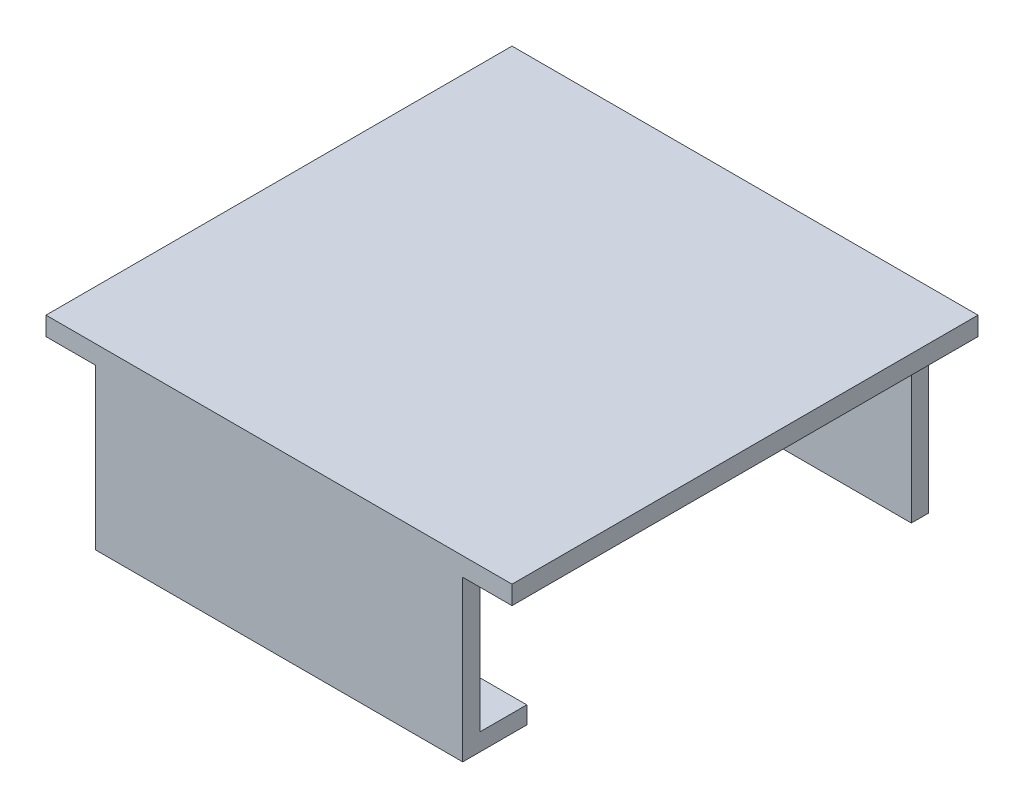
SolidWorks part; units mm, degrees
ref_plane "Plan de face" through (0, 0, 0) normal (0, 0, 1) x (1, 0, 0)
ref_plane "Plan de dessus" through (0, 0, 0) normal (0, 1, 0) x (1, 0, 0)
ref_plane "Plan de droite" through (0, 0, 0) normal (1, 0, 0) x (0, 0, -1)
sketch "Esquisse1" plane through (0, 0, 0) normal (0, 1, 0) x (1, 0, 0)
  line L1 (0, 0) -> (50, 0)
  line L2 (0, 0) -> (0, 50)
  line L3 (0, 50) -> (50, 50)
  line L4 (50, 0) -> (50, 50)
extrude "Boss.-Extru.1" add sketch "Esquisse1" along normal blind 2 contours L2 L3 L4 L1
sketch "Esquisse3" plane through (0, 0, 0) normal (0, -1, 0) x (1, 0, 0)
  line L0 (0, -50) -> (50, -50) construction
  line L2 (5.285, -50) -> (44.715, -50)
  line L4 (5.285, -50) -> (5.285, -48.13)
  line L5 (0, 0) -> (50, 0) construction
  line L6 (5.285, -48.13) -> (44.715, -48.13)
  line L7 (5.285, -1.87) -> (44.715, -1.87)
  line L8 (5.285, -1.87) -> (5.285, 0)
  line L9 (5.285, 0) -> (44.715, 0)
  line L10 (44.715, -1.87) -> (44.715, 0)
  line L11 (44.715, -50) -> (44.715, -48.13)
extrude "Boss.-Extru.2" add sketch "Esquisse3" along normal blind 17.16
sketch "Esquisse4" plane through (0, 0, -1.87) normal (0, 0, -1) x (-1, 0, 0)
  line L0 (-5.285, -17.16) -> (-5.285, 0) construction
  line L1 (-44.715, -17.16) -> (-5.285, -17.16)
  line L2 (-44.715, -17.16) -> (-44.715, -15.29)
  line L3 (-44.715, -15.29) -> (-5.285, -15.29)
  line L4 (-5.285, -17.16) -> (-5.285, -15.29)
extrude "Boss.-Extru.3" add sketch "Esquisse4" along normal blind 5 contours L3 L4 L1 L2
hole_wizard "Dégagement M31" positions "Esquisse3D1" profile "Esquisse5" hole size "M3" standard "Ansi Metric"
sketch3d "Esquisse3D1"
  line L0 (44.715, -15.29, -6.87) -> (5.285, -15.29, -6.87) construction
  line L1 (5.285, -15.29, -6.87) -> (5.285, -15.29, -1.87) construction
  line L2 (44.715, -15.29, -6.87) -> (44.715, -15.29, -1.87) construction
  point P0 (36.195, -15.29, -4.37)
  point P2 (13.805, -15.29, -4.37)
  dimension "D1" = 2.5
  dimension "D2" = 8.52
  dimension "D3" = 2.5
  dimension "D4" = 8.52
sketch "Esquisse5" plane through (36.195, -15.29, -4.37) normal (1, 0, 0) x (0, 0, 1)
  line L0 (0, 0) -> (0, 3.0715)
  line L1 (0, 3.0715) -> (1.8, 1.99)
  line L2 (1.8, 1.99) -> (1.8, 0)
  line L5 (1.8, 0) -> (0, 0)
  line L10 (0, 3.0715) -> (-1.8, 1.99) construction
  line L11 (0, -6.35) -> (0, 107.95) construction
  dimension "Diamètre du perçage" = 3.6
  dimension "Profondeur du perçage" = 1.99
  dimension "Angle de pointe" = 118
sketch "Esquisse7" plane through (0, -17.16, 0) normal (0, -1, 0) x (1, 0, 0)
  line L1 (5.285, -48.13) -> (44.715, -48.13)
  line L2 (5.285, -48.13) -> (5.285, -50)
  line L3 (5.285, -50) -> (44.715, -50)
  line L4 (44.715, -48.13) -> (44.715, -50)
extrude "Boss.-Extru.4" add sketch "Esquisse7" along normal blind 1.87
